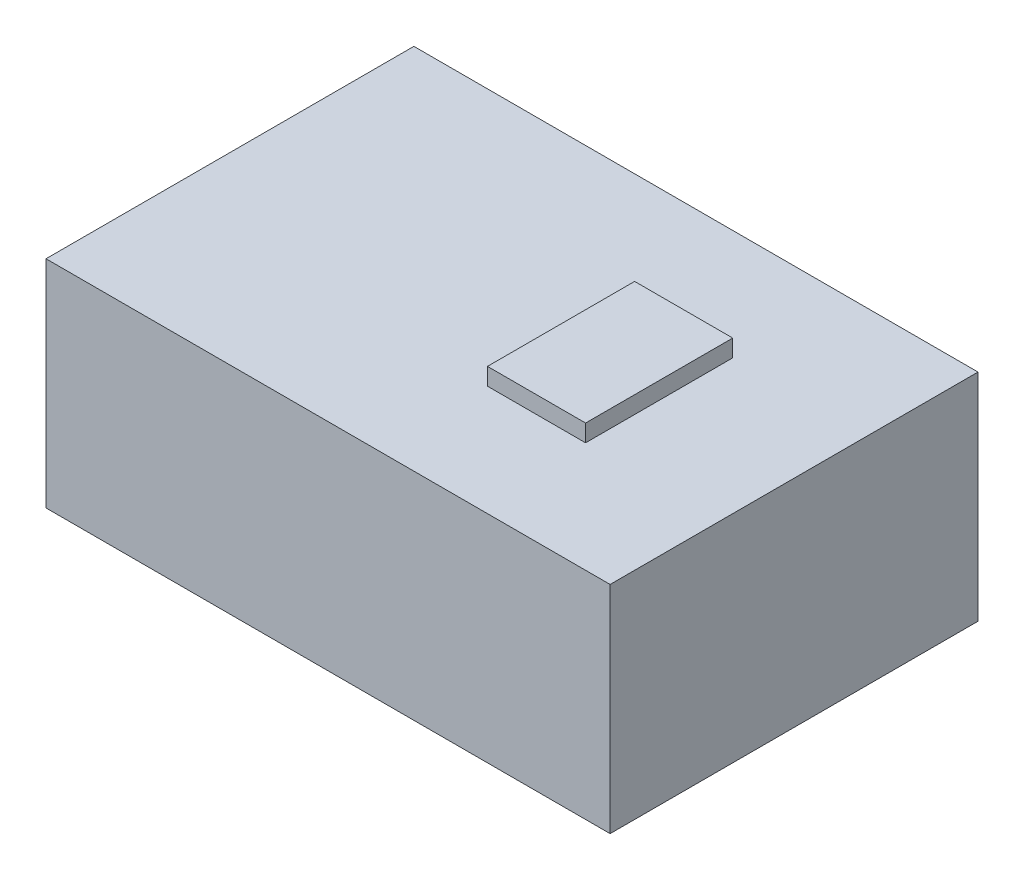
SolidWorks part; units mm, degrees
ref_plane "Front Plane" through (0, 0, 0) normal (0, 0, 1) x (1, 0, 0)
ref_plane "Top Plane" through (0, 0, 0) normal (0, 1, 0) x (1, 0, 0)
ref_plane "Right Plane" through (0, 0, 0) normal (1, 0, 0) x (0, 0, -1)
ref_plane "Plane1" through (0, 0, 11) normal (0, 0, 1) x (1, 0, 0)
sketch "Sketch1" plane through (0, 0, 11) normal (0, 0, 1) x (1, 0, 0)
  line L1 (-31, -126.5) -> (15, -126.5)
  line L2 (-31, -126.5) -> (-31, -108.9)
  line L3 (-31, -108.9) -> (15, -108.9)
  line L4 (15, -126.5) -> (15, -108.9)
  line L5 (-31, -126.5) -> (15, -108.9) construction
  line L6 (-31, -108.9) -> (15, -126.5) construction
  point P0 (-8, -117.7)
extrude "Boss-Extrude1" add sketch "Sketch1" along normal blind 30
ref_plane "Plane2" through (0, 0, 20) normal (0, 0, 1) x (1, 0, 0)
sketch "Sketch2" plane through (0, 0, 20) normal (0, 0, 1) x (1, 0, 0)
  line L1 (-4, -108.9) -> (4, -108.9)
  line L2 (-4, -108.9) -> (-4, -107.5)
  line L3 (-4, -107.5) -> (4, -107.5)
  line L4 (4, -108.9) -> (4, -107.5)
  line L5 (-4, -108.9) -> (4, -107.5) construction
  line L6 (-4, -107.5) -> (4, -108.9) construction
  point P0 (0, -108.2)
extrude "Boss-Extrude2" add sketch "Sketch2" along normal blind 12
